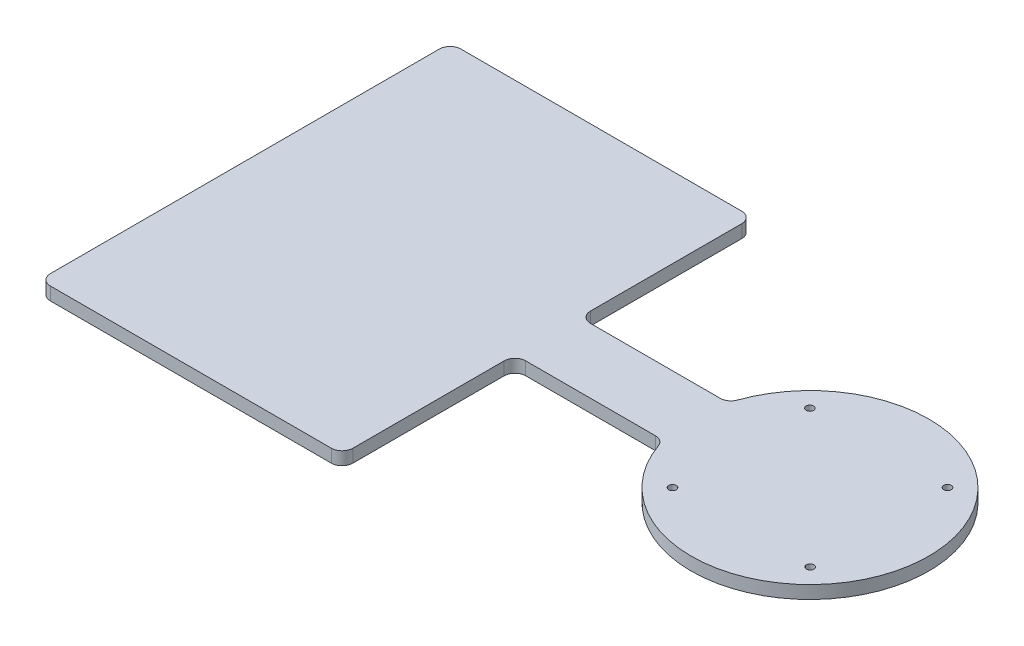
SolidWorks part; units mm, degrees
ref_plane "Front Plane" through (0, 0, 0) normal (0, 0, 1) x (1, 0, 0)
ref_plane "Top Plane" through (0, 0, 0) normal (0, 1, 0) x (1, 0, 0)
ref_plane "Right Plane" through (0, 0, 0) normal (1, 0, 0) x (0, 0, -1)
sketch "Sketch1" plane through (0, 0, 0) normal (0, 1, 0) x (1, 0, 0)
  line L0 (-1006.3103, 0) -> (49309.2058, 0) construction
  line L1 (0, -1006.3103) -> (0, 49309.2058) construction
  line L2 (-56.5685, -15) -> (-116.5685, -15)
  line L3 (-126.5685, 95) -> (-256.5685, 95)
  line L4 (-121.5685, -20) -> (-121.5685, -90)
  line L5 (-126.5685, -95) -> (-256.5685, -95)
  line L6 (-261.5685, -90) -> (-261.5685, 90)
  line L7 (-56.5685, 15) -> (-116.5685, 15)
  line L8 (-121.5685, 20) -> (-121.5685, 90)
  circle A0 centre (31.8513, -31.7883) radius 1.75
  arc A4 (-51.8545, -18.3333) -> (-51.8545, 18.3333) centre (0, 0) ccw
  circle A5 centre (31.7883, 31.8513) radius 1.75
  circle A6 centre (-31.8513, 31.7883) radius 1.75
  circle A7 centre (-31.7883, -31.8513) radius 1.75
  arc A8 (-51.8545, 18.3333) -> (-56.5685, 15) centre (-56.5685, 20) cw
  arc A9 (-51.8545, -18.3333) -> (-56.5685, -15) centre (-56.5685, -20) ccw
  arc A10 (-256.5685, 95) -> (-261.5685, 90) centre (-256.5685, 90) ccw
  arc A11 (-126.5685, 95) -> (-121.5685, 90) centre (-126.5685, 90) cw
  arc A12 (-256.5685, -95) -> (-261.5685, -90) centre (-256.5685, -90) cw
  arc A13 (-126.5685, -95) -> (-121.5685, -90) centre (-126.5685, -90) ccw
  arc A14 (-121.5685, -20) -> (-116.5685, -15) centre (-116.5685, -20) cw
  arc A15 (-121.5685, 20) -> (-116.5685, 15) centre (-116.5685, 20) ccw
  point P10 (0, 0)
  point P19 (0, 0)
  point P24 (-261.5685, 0)
  point P35 (-52.915, 15)
  point P38 (-52.915, -15)
  point P41 (-261.5685, 95)
  point P44 (-121.5685, 95)
  point P47 (-261.5685, -95)
  point P50 (-121.5685, -95)
  point P53 (-121.5685, -15)
  point P56 (-121.5685, 15)
  dimension "D2" = 3.5
  dimension "D3" = 110
  dimension "D8" = 5
  dimension "D9" = 5
  dimension "D1" = 45
  dimension "D5" = 15
  dimension "D6" = 180
  dimension "D7" = 140
  dimension "D10" = 60
  dimension "D4" = 4
extrude "Boss-Extrude1" add sketch "Sketch1" along normal blind 6
